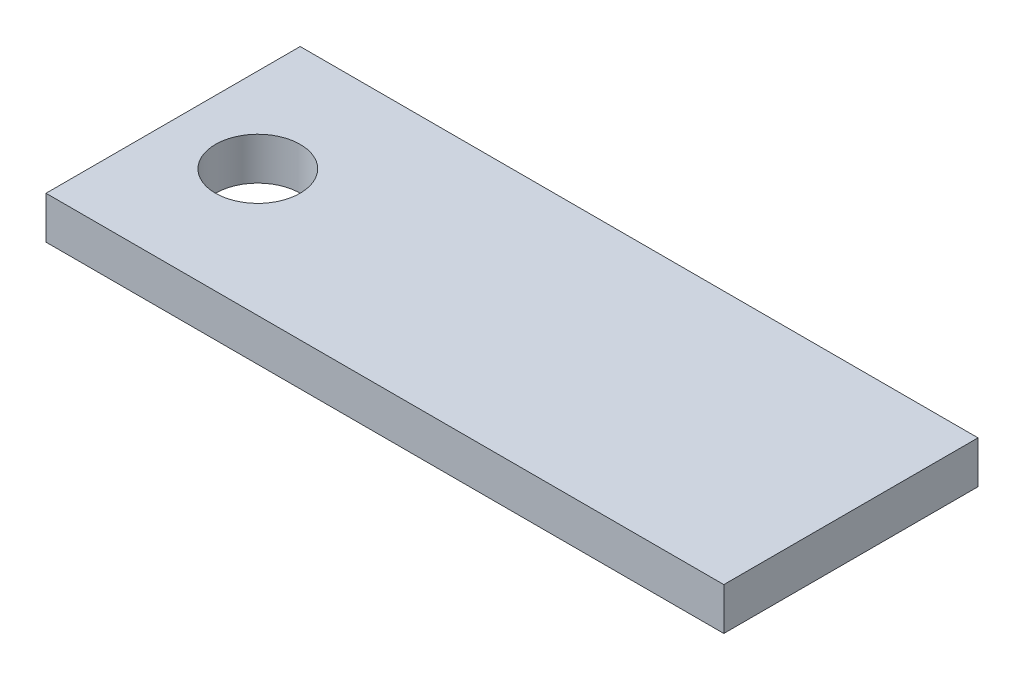
SolidWorks part; units mm, degrees
ref_plane "Front Plane" through (0, 0, 0) normal (0, 0, 1) x (1, 0, 0)
ref_plane "Top Plane" through (0, 0, 0) normal (0, 1, 0) x (1, 0, 0)
ref_plane "Right Plane" through (0, 0, 0) normal (1, 0, 0) x (0, 0, -1)
sketch "Sketch1" plane through (0, 0, 0) normal (0, 1, 0) x (1, 0, 0)
  line L1 (-50.8, -19.05) -> (50.8, -19.05)
  line L2 (-50.8, -19.05) -> (-50.8, 19.05)
  line L3 (-50.8, 19.05) -> (50.8, 19.05)
  line L4 (50.8, -19.05) -> (50.8, 19.05)
  line L5 (-50.8, -19.05) -> (50.8, 19.05) construction
  line L6 (-50.8, 19.05) -> (50.8, -19.05) construction
  point P0 (0, 0)
  dimension "D1" = 38.1
  dimension "D2" = 101.6
extrude "Boss-Extrude1" add sketch "Sketch1" along normal blind 6.35
sketch "Sketch2" plane through (0, 6.35, 0) normal (0, 1, 0) x (1, 0, 0)
  line L0 (-3.4925, 0) -> (3.4925, 0) construction
  line L1 (-50.8, 19.05) -> (-50.8, -19.05) construction
  circle A0 centre (-38.1, 0) radius 6.35
  dimension "D1" = 12.7
  dimension "D2" = 12.7
extrude "Cut-Extrude1" cut sketch "Sketch2" against normal through all
